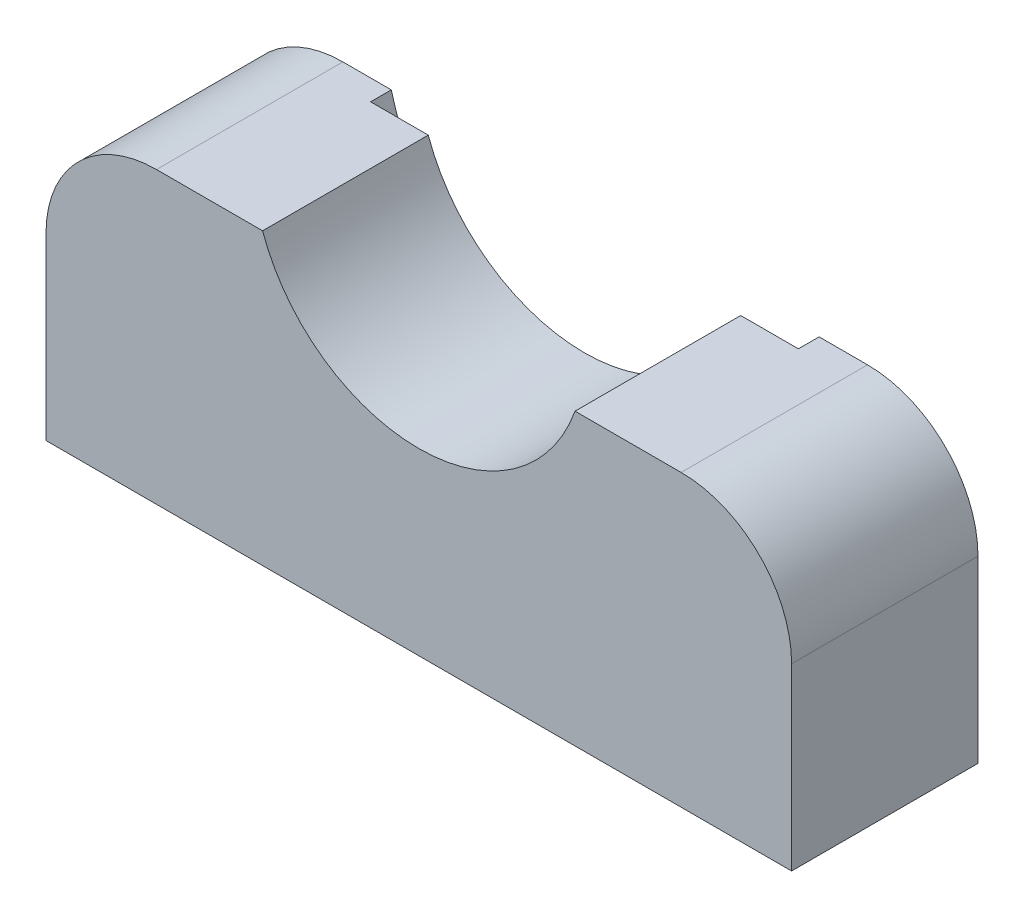
SolidWorks part; units mm, degrees
ref_plane "Front Plane" through (0, 0, 0) normal (0, 0, 1) x (1, 0, 0)
ref_plane "Top Plane" through (0, 0, 0) normal (0, 1, 0) x (1, 0, 0)
ref_plane "Right Plane" through (0, 0, 0) normal (1, 0, 0) x (0, 0, -1)
sketch "Sketch1" plane through (0, 0, 0) normal (0, 0, 1) x (1, 0, 0)
  line L1 (0, 0) -> (-27, 0)
  line L2 (0, 0) -> (0, 12.5)
  line L3 (0, 12.5) -> (-27, 12.5)
  line L4 (-27, 0) -> (-27, 12.5)
  circle A0 centre (-13.5, 12.5) radius 6
  dimension "D3" = 12
  dimension "D1" = 27
  dimension "D2" = 12.5
extrude "Boss-Extrude1" add sketch "Sketch1" along normal blind 6.75 contours A0 L3 L4 L1 L2
sketch "Sketch3" plane through (0, 0, 0) normal (0, 0, -1) x (-1, 0, 0)
  circle A0 centre (13.5, 12.5) radius 8
  dimension "D1" = 16
extrude "Cut-Extrude2" cut sketch "Sketch3" against normal blind 0.75
sketch "Sketch4" plane through (0, 0, 6.75) normal (0, 0, 1) x (1, 0, 0)
  line L0 (-27, 0) -> (-27, 12.5) construction
  line L1 (0, 12.5) -> (-27, 12.5)
  line L2 (0, 12.5) -> (0, 10.5)
  line L3 (0, 10.5) -> (-27, 10.5)
  line L4 (-27, 12.5) -> (-27, 10.5)
  line L5 (0, 0) -> (0, 12.5) construction
  line L6 (0, 12.5) -> (-7.5, 12.5) construction
  dimension "D1" = 2
extrude "Cut-Extrude3" cut sketch "Sketch4" against normal blind 9
sketch "Sketch5" plane through (0, 0, 0) normal (0, -1, 0) x (1, 0, 0)
  line L0 (-27, 3.375) -> (0, 3.375) construction
  line L1 (-27, 6.75) -> (-27, 0) construction
  line L2 (0, 6.75) -> (0, 0) construction
  circle A0 centre (-23.5, 3.375) radius 1.5
  circle A1 centre (-3.5, 3.375) radius 1.5
  dimension "D1" = 3
  dimension "D2" = 3.5
  dimension "D3" = 3.5
extrude "Cut-Extrude4" [suppressed] cut sketch "Sketch5" against normal blind 16
fillet "Fillet1" radius 4 2 edges at (-27, 10.5, 3.375) (0, 10.5, 3.375)
